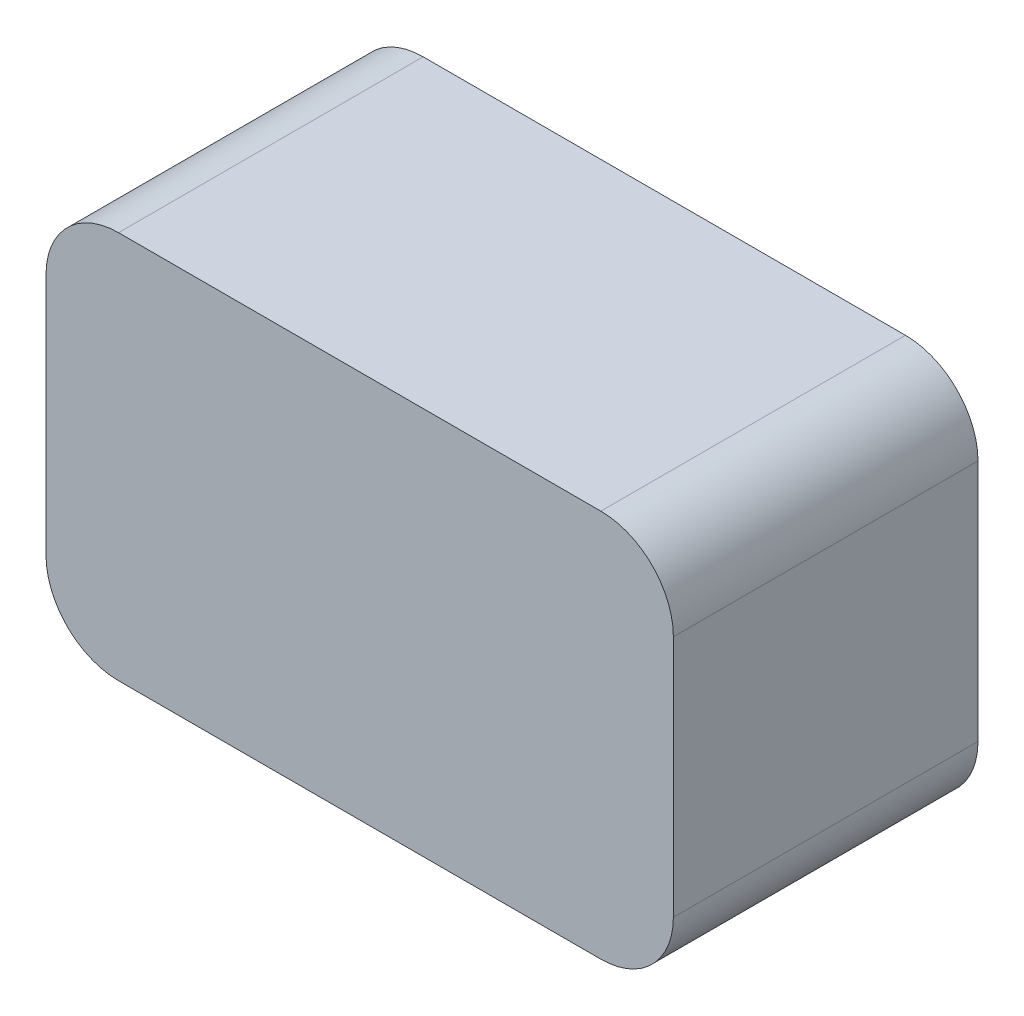
SolidWorks part; units mm, degrees
ref_plane "Płaszczyzna przednia" through (0, 0, 0) normal (0, 0, 1) x (1, 0, 0)
ref_plane "Płaszczyzna górna" through (0, 0, 0) normal (0, 1, 0) x (1, 0, 0)
ref_plane "Płaszczyzna prawa" through (0, 0, 0) normal (1, 0, 0) x (0, 0, -1)
sketch "Szkic1" plane through (0, 0, 0) normal (0, 0, 1) x (1, 0, 0)
  line L1 (-42.2351, 15.4291) -> (24.2649, 15.4291)
  line L2 (-52.2351, 5.4291) -> (-52.2351, -28.0709)
  line L3 (-42.2351, -38.0709) -> (24.2649, -38.0709)
  line L4 (34.2649, 5.4291) -> (34.2649, -28.0709)
  arc A0 (24.2649, 15.4291) -> (34.2649, 5.4291) centre (24.2649, 5.4291) cw
  arc A1 (24.2649, -38.0709) -> (34.2649, -28.0709) centre (24.2649, -28.0709) ccw
  arc A2 (-52.2351, -28.0709) -> (-42.2351, -38.0709) centre (-42.2351, -28.0709) ccw
  arc A3 (-42.2351, 15.4291) -> (-52.2351, 5.4291) centre (-42.2351, 5.4291) ccw
  point P6 (34.2649, 15.4291)
  point P11 (-52.2351, -38.0709)
  point P14 (-52.2351, 15.4291)
  dimension "D3" = 10
  dimension "D4" = 10
  dimension "D1" = 86.5
  dimension "D2" = 53.5
extrude "Dodanie-wyciągnięcie1" add sketch "Szkic1" along normal blind 42
